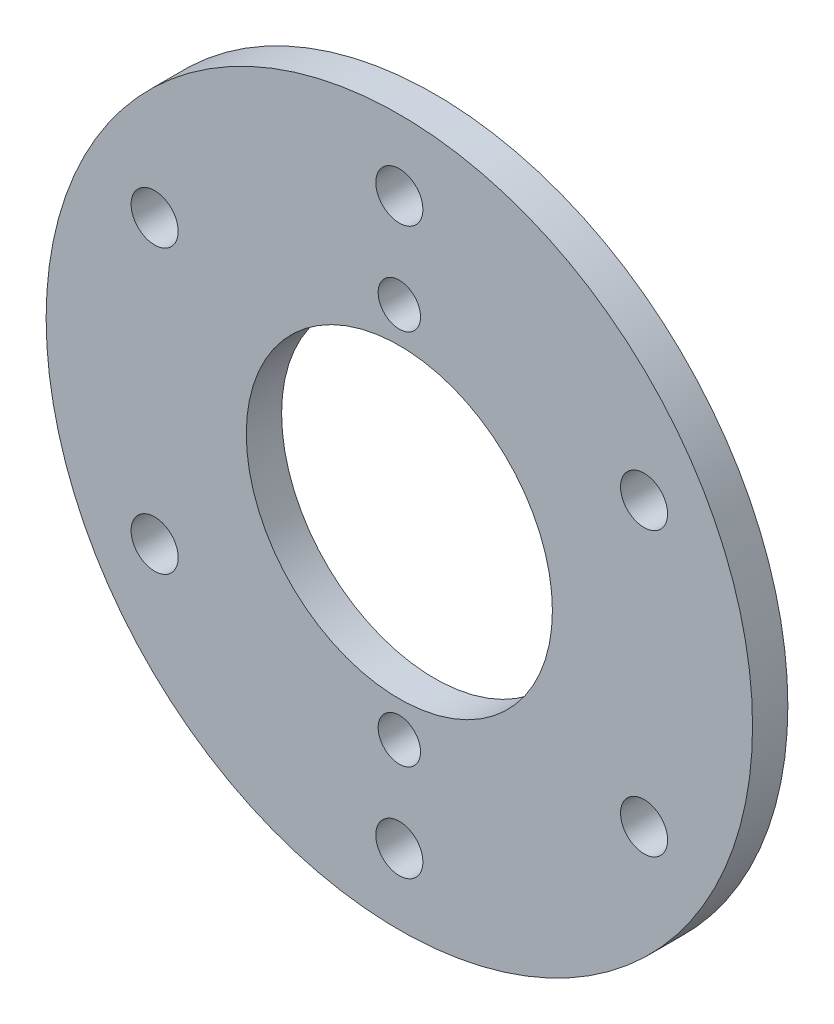
SolidWorks part; units mm, degrees
material "Rubber"
ref_plane "Front Plane" through (0, 0, 0) normal (0, 0, 1) x (1, 0, 0)
ref_plane "Top Plane" through (0, 0, 0) normal (0, 1, 0) x (1, 0, 0)
ref_plane "Right Plane" through (0, 0, 0) normal (1, 0, 0) x (0, 0, -1)
sketch "Sketch1" plane through (0, 0, 0) normal (0, 0, 1) x (1, 0, 0)
  circle A0 centre (0, 0) radius 150
  circle A1 centre (0, 0) radius 65
  circle A2 centre (0, 80) radius 9
  circle A3 centre (0, 120) radius 10
  circle A4 centre (103.923, 60) radius 10
  circle A5 centre (103.923, -60) radius 10
  circle A6 centre (0, -120) radius 10
  circle A7 centre (-103.923, -60) radius 10
  circle A8 centre (-103.923, 60) radius 10
  circle A9 centre (0, -80) radius 9
  point P9 (-52.8749, -60)
  point P10 (0, 0)
  point P22 (0, 0)
  dimension "D1" = 300
  dimension "D2" = 130
  dimension "D3" = 20
  dimension "D4" = 80
  dimension "180" = 18
  dimension "D5" = 120
  dimension "D6" = 6
  dimension "D7" = 2
extrude "Boss-Extrude1" add sketch "Sketch1" along normal mid plane 15
